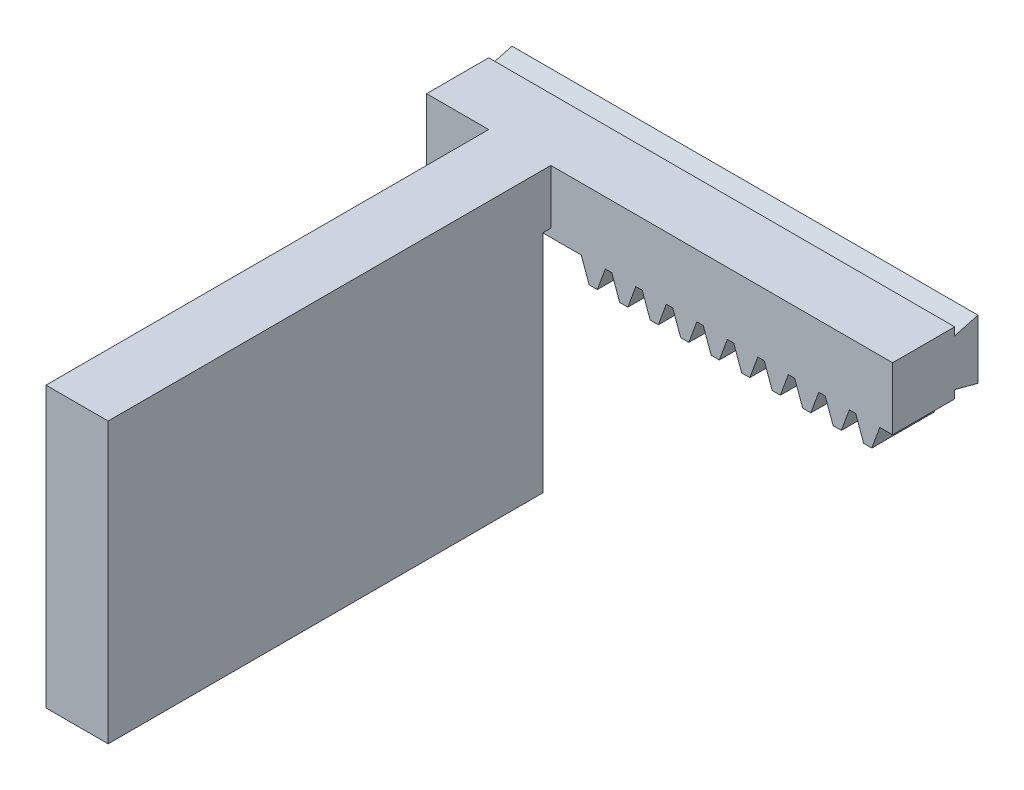
SolidWorks part; units mm, degrees
ref_plane "Front Plane" through (0, 0, 0) normal (0, 0, 1) x (1, 0, 0)
ref_plane "Top Plane" through (0, 0, 0) normal (0, 1, 0) x (1, 0, 0)
ref_plane "Right Plane" through (0, 0, 0) normal (1, 0, 0) x (0, 0, -1)
sketch "Rack profile m1.25" plane through (0, 0, 0) normal (0, 0, 1) x (1, 0, 0)
  line L0 (-8, 21) -> (52, 21)
  line L1 (52, 21) -> (52, 12.9625)
  line L2 (52, 12.9625) -> (50.3569, 12.9625)
  line L3 (50.3569, 12.9625) -> (49.3332, 10.15)
  line L4 (49.3332, 10.15) -> (48.2796, 10.15)
  line L5 (48.2796, 10.15) -> (47.256, 12.9625)
  line L6 (47.256, 12.9625) -> (46.4299, 12.9625)
  line L7 (46.4299, 12.9625) -> (45.4062, 10.15)
  line L8 (45.4062, 10.15) -> (44.3526, 10.15)
  line L9 (44.3526, 10.15) -> (43.329, 12.9625)
  line L10 (43.329, 12.9625) -> (42.5029, 12.9625)
  line L11 (42.5029, 12.9625) -> (41.4792, 10.15)
  line L12 (41.4792, 10.15) -> (40.4256, 10.15)
  line L13 (40.4256, 10.15) -> (39.402, 12.9625)
  line L14 (39.402, 12.9625) -> (38.5759, 12.9625)
  line L15 (38.5759, 12.9625) -> (37.5522, 10.15)
  line L16 (37.5522, 10.15) -> (36.4987, 10.15)
  line L17 (36.4987, 10.15) -> (35.475, 12.9625)
  line L18 (35.475, 12.9625) -> (34.6489, 12.9625)
  line L19 (34.6489, 12.9625) -> (33.6252, 10.15)
  line L20 (33.6252, 10.15) -> (32.5717, 10.15)
  line L21 (32.5717, 10.15) -> (31.548, 12.9625)
  line L22 (31.548, 12.9625) -> (30.7219, 12.9625)
  line L23 (30.7219, 12.9625) -> (29.6982, 10.15)
  line L24 (29.6982, 10.15) -> (28.6447, 10.15)
  line L25 (28.6447, 10.15) -> (27.621, 12.9625)
  line L26 (27.621, 12.9625) -> (26.7949, 12.9625)
  line L27 (26.7949, 12.9625) -> (25.7713, 10.15)
  line L28 (25.7713, 10.15) -> (24.7177, 10.15)
  line L29 (24.7177, 10.15) -> (23.694, 12.9625)
  line L30 (23.694, 12.9625) -> (22.8679, 12.9625)
  line L31 (22.8679, 12.9625) -> (21.8443, 10.15)
  line L32 (21.8443, 10.15) -> (20.7907, 10.15)
  line L33 (20.7907, 10.15) -> (19.767, 12.9625)
  line L34 (19.767, 12.9625) -> (18.9409, 12.9625)
  line L35 (18.9409, 12.9625) -> (17.9173, 10.15)
  line L36 (17.9173, 10.15) -> (16.8637, 10.15)
  line L37 (16.8637, 10.15) -> (15.84, 12.9625)
  line L38 (15.84, 12.9625) -> (15.0139, 12.9625)
  line L39 (15.0139, 12.9625) -> (13.9903, 10.15)
  line L40 (13.9903, 10.15) -> (12.9367, 10.15)
  line L41 (12.9367, 10.15) -> (11.913, 12.9625)
  line L42 (11.913, 12.9625) -> (-8, 12.9625)
  line L43 (-8, 12.9625) -> (-8, 21)
extrude "Rack body 8mm" add sketch "Rack profile m1.25" along normal blind 8 contours L0 L1 L2 L3 L4 L5 L6 L7 L8 L9 L10 L11 L12 L13 L14 L15 L16 L17 L18 L19 L20 L21 L22 L23 L24 L25 L26 L27 L28 L29 L30 L31 L32 L33 L34 L35 L36 L37 L38 L39 L40 L41 L42 L43
sketch "Finger Arm Profile" plane through (0, 0, 0) normal (1, 0, 0) x (0, 0, -1)
  line L0 (-2, 21) -> (-65, 21)
  line L1 (-65, 21) -> (-65, -15)
  line L2 (-65, -15) -> (-9, -15)
  line L3 (-9, -15) -> (-9, 14)
  line L4 (-9, 14) -> (-2, 14)
  line L5 (-2, 14) -> (-2, 21)
extrude "Finger arm 8mm" add sketch "Finger Arm Profile" along normal blind 8
sketch "Dovetail Tongue" plane through (0, 0, 0) normal (1, 0, 0) x (0, 0, -1)
  line L0 (0, 14) -> (0, 20)
  line L1 (0, 20) -> (3, 20.8)
  line L2 (3, 20.8) -> (3, 13.2)
  line L3 (3, 13.2) -> (0, 14)
extrude "Dovetail Tongue 52 + 8" add sketch "Dovetail Tongue" along normal blind 52 and the other way blind 8
sketch "Sensor Pocket Placeholder" plane through (0, 0, 0) normal (1, 0, 0) x (0, 0, -1)
  circle A0 centre (-48, 0) radius 10
extrude "Sensor Pocket Cut" cut sketch "Sensor Pocket Placeholder" along normal blind 1.5
sketch "Neoprened pad sketch" plane through (0, 0, 0) normal (1, 0, 0) x (0, 0, -1)
  line L0 (-33, -15) -> (-63, -15)
  line L1 (-63, -15) -> (-63, 15)
  line L2 (-63, 15) -> (-33, 15)
  line L3 (-33, 15) -> (-33, -15)
extrude "Neoprene pad (not printed)" add sketch "Neoprened pad sketch" against normal blind 1.5 separate body
